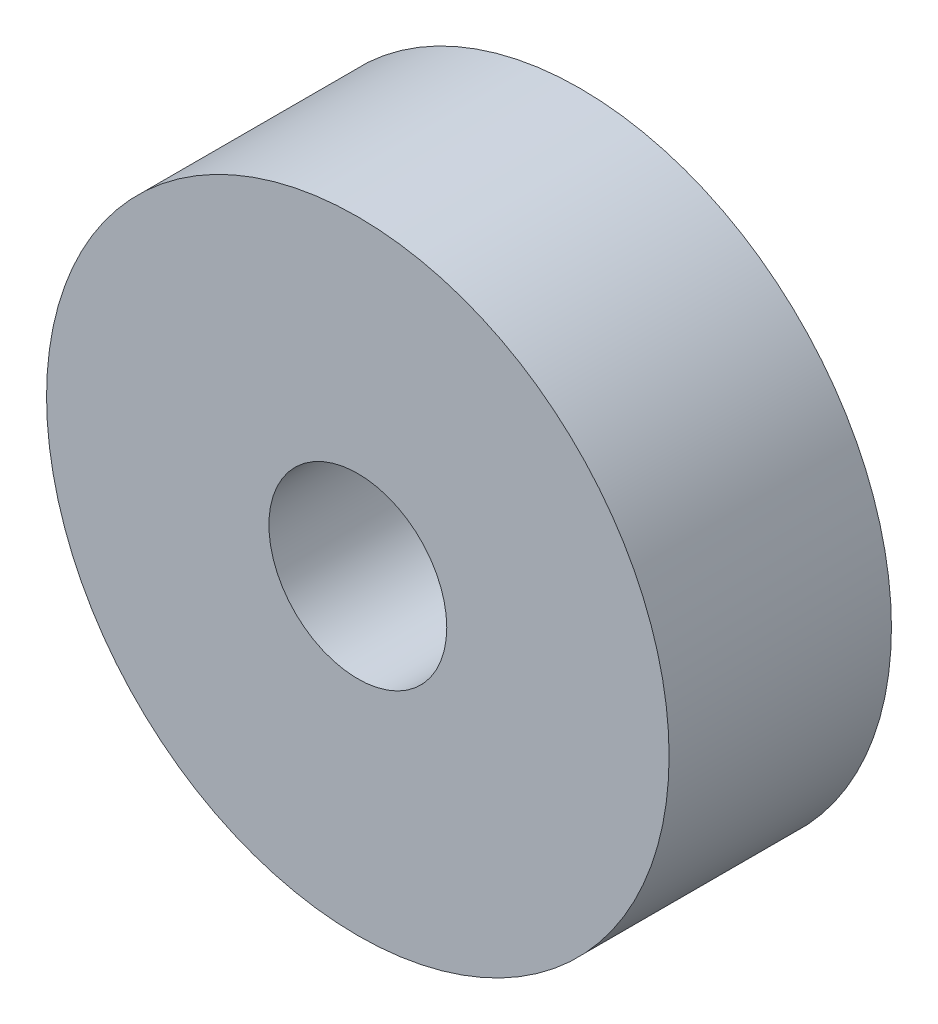
SolidWorks part; units mm, degrees
ref_plane "Plan de face" through (0, 0, 0) normal (0, 0, 1) x (1, 0, 0)
ref_plane "Plan de dessus" through (0, 0, 0) normal (0, 1, 0) x (1, 0, 0)
ref_plane "Plan de droite" through (0, 0, 0) normal (1, 0, 0) x (0, 0, -1)
sketch "Esquisse1" plane through (0, 0, 0) normal (0, 0, 1) x (1, 0, 0)
  circle A0 centre (0, 0) radius 2
  circle A1 centre (0, 0) radius 7
  dimension "D1" = 4
  dimension "D2" = 14
extrude "Boss.-Extru.1" add sketch "Esquisse1" along normal blind 5
